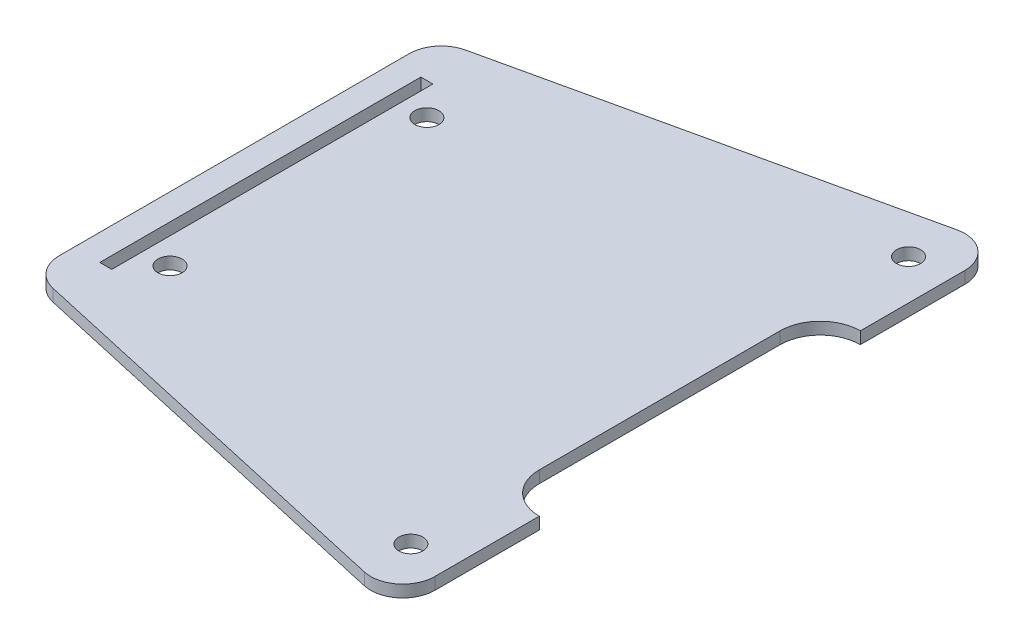
SolidWorks part; units mm, degrees
material "Thornel Mat VMA"
ref_plane "前视基准面" through (0, 0, 0) normal (0, 0, 1) x (1, 0, 0)
ref_plane "上视基准面" through (0, 0, 0) normal (0, 1, 0) x (1, 0, 0)
ref_plane "右视基准面" through (0, 0, 0) normal (1, 0, 0) x (0, 0, -1)
other "Configuration Table"
sketch "草图1" plane through (0, 0, 0) normal (0, 1, 0) x (1, 0, 0)
  line L8 (-1000, 0) -> (49000, 0) construction
  line L9 (0, -1000) -> (0, 49000) construction
  line L10 (-33, 25) -> (-33, -25)
  line L11 (25, 38) -> (25, -38)
  line L12 (-33, 25) -> (25, 38)
  line L13 (25, -38) -> (-33, -25)
  line L15 (-29.75, -20) -> (-28.25, -20)
  line L16 (-29.75, -20) -> (-29.75, 20)
  line L17 (-29.75, 20) -> (-28.25, 20)
  line L18 (-28.25, -20) -> (-28.25, 20)
  line L19 (-29.75, -20) -> (-28.25, 20) construction
  line L20 (-29.75, 20) -> (-28.25, -20) construction
  circle A0 centre (-25, 16) radius 1.5
  circle A1 centre (20, 31) radius 1.5
  circle A2 centre (20, -31) radius 1.5
  circle A3 centre (-25, -16) radius 1.5
  point P9 (-33, 0)
  point P11 (25, 0)
  point P20 (-29, 0)
  dimension "D7" = 16
  dimension "D8" = 31
  dimension "D9" = 5
  dimension "D10" = 45
  dimension "D11" = 3
  dimension "D12" = 3
  dimension "D13" = 1.5
  dimension "D1" = 50
  dimension "D2" = 76
  dimension "D3" = 0
  dimension "D4" = 0
  dimension "D5" = 58
  dimension "D6" = 25
  dimension "D14" = 4
  dimension "D15" = 40
extrude "凸台-拉伸1" add sketch "草图1" along normal blind 1.5
sketch "草图3" plane through (0, 1.5, 0) normal (0, 1, 0) x (1, 0, 0)
  line L0 (25, -15) -> (25, 15) construction
  line L1 (20, -15) -> (20, 15)
  line L2 (30, -15) -> (30, 15)
  line L3 (25, -38) -> (25, 38) construction
  arc A0 (20, -15) -> (30, -15) centre (25, -15) ccw
  arc A1 (30, 15) -> (20, 15) centre (25, 15) ccw
  point P2 (25, 0)
  dimension "D1" = 5
  dimension "D2" = 30
  dimension "D3" = 0
  dimension "D4" = 0
extrude "切除-拉伸2" cut sketch "草图3" against normal through all
fillet "圆角1" radius 4 4 edges at (-33, 0.75, 25) (25, 0.75, 38) (25, 0.75, -38) (-33, 0.75, -25)
